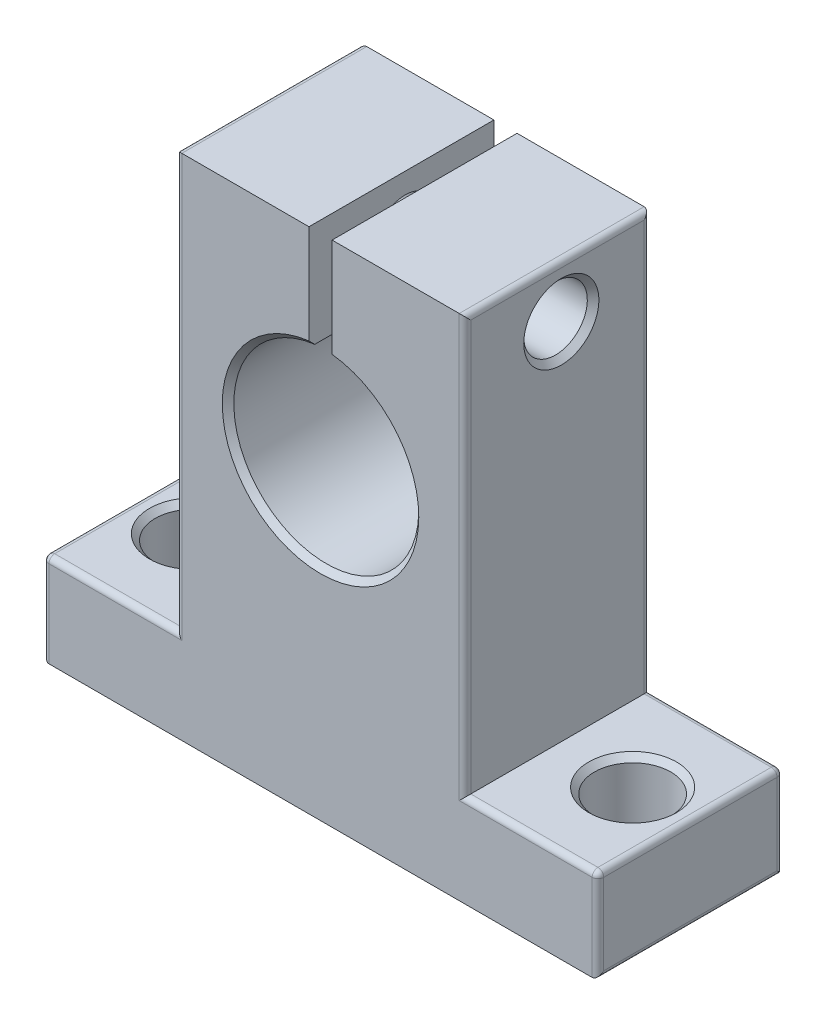
SolidWorks part; units mm, degrees
material "1060 Alloy"
ref_plane "Front Plane" through (0, 0, 0) normal (0, 0, 1) x (1, 0, 0)
ref_plane "Top Plane" through (0, 0, 0) normal (0, 1, 0) x (1, 0, 0)
ref_plane "Right Plane" through (0, 0, 0) normal (1, 0, 0) x (0, 0, -1)
sketch "Sketch1" plane through (0, 0, 0) normal (0, 0, 1) x (1, 0, 0)
  line L0 (0, 0) -> (-50000, 0) construction
  line L1 (0, 0) -> (0, 50000) construction
  line L2 (-24, -4) -> (-24, 4)
  line L3 (-24, 4) -> (-12.5, 4)
  line L4 (-12.5, 4) -> (-12.5, 40)
  line L5 (-12.5, 40) -> (-1, 40)
  line L6 (12.5, 40) -> (12.5, 4)
  line L7 (12.5, 4) -> (24, 4)
  line L8 (24, 4) -> (24, -4)
  line L9 (24, -4) -> (-24, -4)
  line L10 (19, -3) -> (19, 3) construction
  line L11 (-19, -3) -> (-19, 3) construction
  line L12 (-1, 40) -> (-1, 30.9373)
  line L13 (1, 40) -> (1, 30.9373)
  line L14 (1, 40) -> (12.5, 40)
  arc A0 (-1, 30.9373) -> (1, 30.9373) centre (0, 23) ccw
  point P8 (-24, 0)
  point P15 (0, -4)
  point P21 (19, 0)
  dimension "Shaft Diameter" = 16
  dimension "W" = 48
  dimension "P" = 25
  dimension "F" = 44
  dimension "G" = 8
  dimension "B" = 38
  dimension "D1" = 2
  dimension "h" = 27
extrude "Boss-Extrude1" add sketch "Sketch1" along normal mid plane 16
sketch "Sketch2" plane through (0, 4, 0) normal (0, 1, 0) x (1, 0, 0)
  line L0 (0, 0) -> (50000, 0) construction
  line L1 (0.3141, 0) -> (-49999.6859, 0) construction
  line L2 (0, 2.4842) -> (0, 50002.4842) construction
  circle A0 centre (19, 0) radius 3.3
  circle A1 centre (-19, 0) radius 3.3
  dimension "B" = 38
  dimension "S" = 6.6
extrude "Cut-Extrude1" cut sketch "Sketch2" against normal through all
sketch "Sketch5" plane through (-1, 0, 0) normal (1, 0, 0) x (0, 0, -1)
  line L0 (-8, 35.4686) -> (8, 35.4686) construction
  line L1 (8, 30.9373) -> (8, 40) construction
  line L2 (0, 40) -> (0, 30.9373) construction
  line L3 (-8, 40) -> (8, 40) construction
  line L4 (-8, 30.9373) -> (8, 30.9373) construction
  line L5 (-8, 30.9373) -> (-8, 40) construction
  circle A0 centre (0.3307, 35.4686) radius 2.75
  dimension "Clamping bold" = 5.5
extrude "Cut-Extrude2" cut sketch "Sketch5" against normal through all both and the other way through all
chamfer "Chamfer2" distance 0.5 angle 45 6 edges at (0, 15, -8) (0, 15, 8) (-12.5, 35.4686, -3.0807) (-15.7, 4, 0) (12.5, 35.4686, 2.4193) (15.7, 4, 0)
fillet "Fillet2" radius 0.5 18 edges at (24, -4, 0) (24, 0, 8) (24, 4, 0) (24, 0, -8) (-24, 4, 0) (-24, 0, 8) (-24, -4, 0) (-24, 0, -8) (-18.25, 4, -8) (-18.25, 4, 8) (-12.5, 22, 8) (-12.5, 40, 0) (-12.5, 22, -8) (12.5, 22, -8) (12.5, 22, 8) (18.25, 4, 8) (18.25, 4, -8) (12.5, 40, 0)
equation "\"W\"= \"W@Sketch1\"'Width"
equation "\"B\"= \"B@Sketch1\"'between hold"
equation "\"F\"= \"F@Sketch1\"'Hight"
equation "\"P\"= \"P@Sketch1\""
equation "\"G\"= \"G@Sketch1\""
equation "\"Shaft diameter\"= \"Shaft Diameter@Sketch1\""
equation "\"S\"= 6.6'M6"
equation "\"Clamping bold\"= 5.5'M5"
equation "\"h\"= \"h@Sketch1\""
